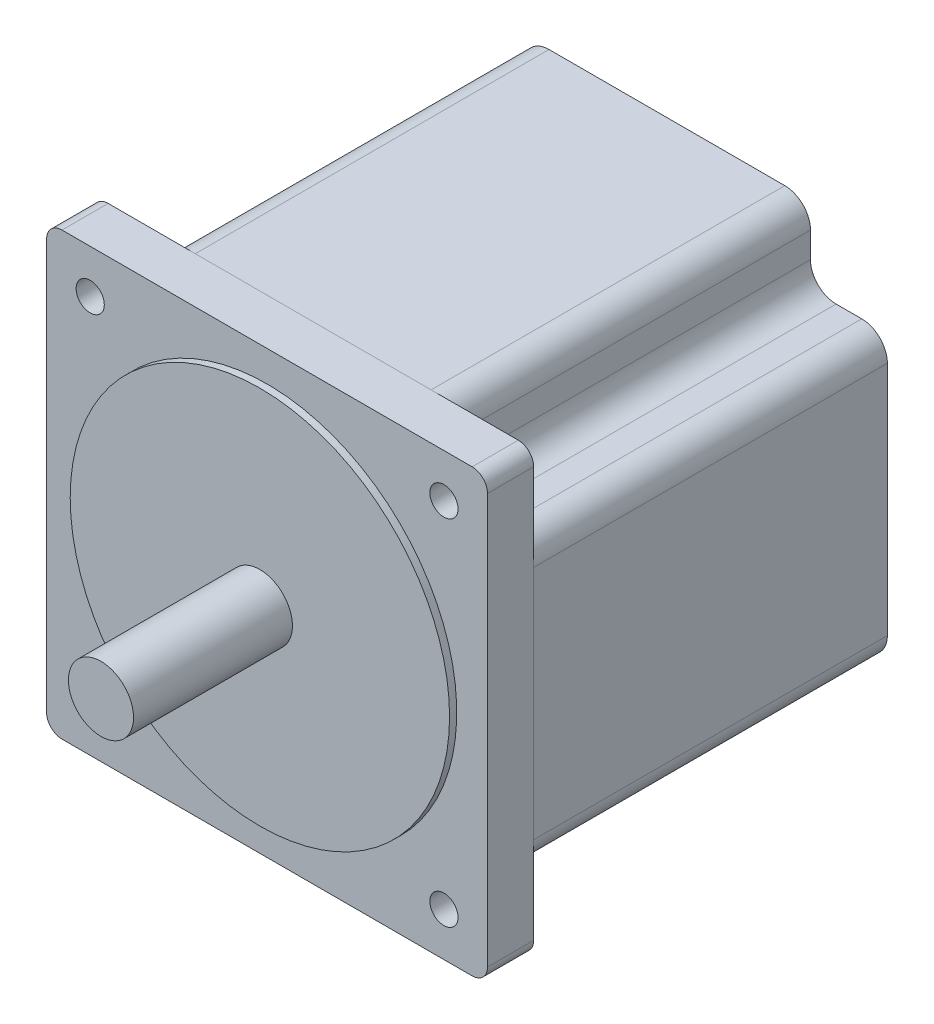
SolidWorks part; units mm, degrees
material "SKD11淬火HRC56-60"
ref_plane "前基準面" through (0, 0, 0) normal (0, 0, 1) x (1, 0, 0)
ref_plane "上基準面" through (0, 0, 0) normal (0, 1, 0) x (1, 0, 0)
ref_plane "右基準面" through (0, 0, 0) normal (1, 0, 0) x (0, 0, -1)
sketch "草图1" plane through (0, 0, 0) normal (0, 0, 1) x (1, 0, 0)
  line L1 (0, 0) -> (86, 0)
  line L2 (0, 0) -> (0, 86)
  line L3 (0, 86) -> (86, 86)
  line L4 (86, 0) -> (86, 86)
  dimension "D1" = 86
extrude "凸台-拉伸1" add sketch "草图1" along normal blind 9
sketch "草图2" plane through (0, 0, 0) normal (0, 0, -1) x (-1, 0, 0)
  line L4 (0, 0) -> (0, 86)
  line L5 (0, 86) -> (-86, 86)
  line L6 (-86, 86) -> (-86, 0)
  line L7 (-86, 0) -> (0, 0)
  line L8 (0, 0) -> (0, 86)
  line L9 (0, 86) -> (-86, 86)
  line L10 (-86, 86) -> (-86, 0)
  line L11 (-86, 0) -> (0, 0)
  dimension "D1" = 0
extrude "凸台-拉伸2" add sketch "草图2" along normal blind 69 separate body
sketch "草图3" plane through (0, 0, 9) normal (0, 0, 1) x (1, 0, 0)
  line L0 (43, 86) -> (43, 0) construction
  line L1 (86, 86) -> (0, 86) construction
  line L2 (0, 0) -> (86, 0) construction
  circle A0 centre (43, 43) radius 37
  dimension "D1" = 74
extrude "凸台-拉伸3" add sketch "草图3" along normal blind 1.4
sketch "草图4" plane through (0, 0, 10.4) normal (0, 0, 1) x (1, 0, 0)
  circle A0 centre (43, 43) radius 6.35
  dimension "D1" = 12.7
extrude "凸台-拉伸4" add sketch "草图4" along normal blind 31
sketch "草图5" plane through (0, 0, 9) normal (0, 0, 1) x (1, 0, 0)
  line L0 (43, 86) -> (43, 0) construction
  line L1 (86, 86) -> (0, 86) construction
  line L2 (0, 0) -> (86, 0) construction
  line L3 (0, 43) -> (86, 43) construction
  line L4 (0, 86) -> (0, 0) construction
  line L5 (86, 0) -> (86, 86) construction
  circle A0 centre (8.5, 77.5) radius 2.75
  circle A1 centre (77.5, 77.5) radius 2.75
  circle A2 centre (77.5, 8.5) radius 2.75
  circle A3 centre (8.5, 8.5) radius 2.75
  dimension "D1" = 5.5
  dimension "D2" = 69
  dimension "D3" = 69
extrude "切除-拉伸1" cut sketch "草图5" against normal blind 10
sketch "草图6" plane through (0, 0, -69) normal (0, 0, -1) x (-1, 0, 0)
  line L0 (-43, 86) -> (-43, 0) construction
  line L1 (-86, 86) -> (-71, 86)
  line L2 (-86, 86) -> (-86, 71)
  line L3 (-86, 71) -> (-71, 71)
  line L4 (-71, 86) -> (-71, 71)
  line L5 (0, 86) -> (-86, 86) construction
  line L6 (-86, 0) -> (0, 0) construction
  line L7 (-86, 43) -> (0, 43) construction
  line L8 (-86, 86) -> (-86, 0) construction
  line L9 (0, 0) -> (0, 86) construction
  line L10 (-15, 86) -> (-15, 71)
  line L11 (0, 71) -> (-15, 71)
  line L12 (0, 86) -> (0, 71)
  line L13 (0, 86) -> (-15, 86)
  line L14 (0, 0) -> (-15, 0)
  line L15 (0, 0) -> (0, 15)
  line L16 (0, 15) -> (-15, 15)
  line L17 (-15, 0) -> (-15, 15)
  line L18 (-71, 0) -> (-71, 15)
  line L19 (-86, 15) -> (-71, 15)
  line L20 (-86, 0) -> (-86, 15)
  line L21 (-86, 0) -> (-71, 0)
  dimension "D1" = 15
extrude "切除-拉伸2" cut sketch "草图6" against normal blind 69
fillet "圆角1" radius 5 12 edges at (71, 0, -34.5) (86, 15, -34.5) (86, 71, -34.5) (71, 86, -34.5) (15, 86, -34.5) (0, 71, -34.5) (0, 15, -34.5) (15, 0, -34.5) (15, 15, -34.5) (71, 15, -34.5) (71, 71, -34.5) (15, 71, -34.5)
sketch "草图7" plane through (0, 0, -69) normal (0, 0, -1) x (-1, 0, 0)
  line L0 (-43, 0) -> (-43, 86) construction
  line L1 (-66, 0) -> (-20, 0) construction
  line L2 (-20, 86) -> (-66, 86) construction
  circle A0 centre (-43, 43) radius 6.35
  dimension "D1" = 12.7
extrude "切除-拉伸3" cut sketch "草图7" against normal blind 1
fillet "圆角2" radius 3 4 edges at (0, 86, 4.5) (86, 86, 4.5) (0, 0, 4.5) (86, 0, 4.5)
